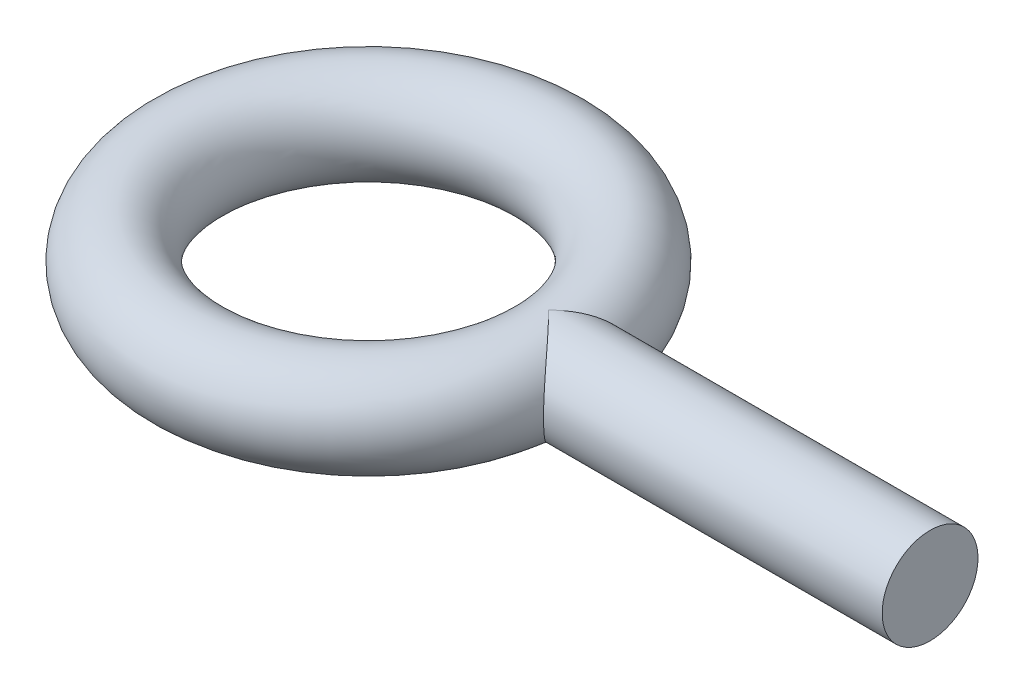
SolidWorks part; units mm, degrees
ref_plane "Front Plane" through (0, 0, 0) normal (0, 0, 1) x (1, 0, 0)
ref_plane "Top Plane" through (0, 0, 0) normal (0, 1, 0) x (1, 0, 0)
ref_plane "Right Plane" through (0, 0, 0) normal (1, 0, 0) x (0, 0, -1)
sketch "layout" plane through (0, 0, 0) normal (0, 1, 0) x (1, 0, 0)
  line L0 (0, 0) -> (37.211, 0) construction
  circle A0 centre (0, 0) radius 15.113 construction
  dimension "D1" = 30.226
  dimension "D2" = 52.324
sketch "Sketch2" plane through (0, 0, 0) normal (0, 0, 1) x (1, 0, 0)
  line L3 (0, 0) -> (0, 6.6909) construction
  line L4 (15.113, 0) -> (-15.113, 0) construction
  circle A0 centre (-11.938, 0) radius 3.175
  point P4 (-15.113, 0)
  dimension "D1" = 6.35
revolve "Revolve1" add sketch "Sketch2" angle 360 about L3
ref_plane "Plane1" through (37.211, 0, 0) normal (1, 0, 0) x (0, 0, -1)
sketch "Sketch3" plane through (37.211, 0, 0) normal (1, 0, 0) x (0, 0, -1)
  circle A0 centre (0, 0) radius 3.175
  dimension "A" = 6.35
extrude "Extrude1" add sketch "Sketch3" against normal up to next
cosmetic thread "Cosmetic Thread1" [suppressed] parameters "D1"=19.05, "D2"=4.7625
sketch "Sketch4" plane through (0, 0, 0) normal (0, 1, 0) x (1, 0, 0)
  line L0 (36.7527, 3.175) -> (37.211, 2.3812)
  line L1 (37.211, 2.3812) -> (37.6693, 3.175)
  line L2 (37.6693, 3.175) -> (37.6693, 4.0915)
  line L3 (37.6693, 4.0915) -> (36.7527, 4.0915)
  line L4 (36.7527, 4.0915) -> (36.7527, 3.175)
  line L5 (0, 0) -> (42.1538, 0) construction
  dimension "D1" = 4.7625
  dimension "D2" = 6.35
revolve "Cut-Revolve1" [suppressed] cut sketch "Sketch4" angle 360 about L5
pattern_linear "LPattern1" [suppressed] count 15 along (1, 0, 0)
equation "\"A@Sketch3\" = \"D1@Sketch2\""
equation "\"D1@Sketch4\" = \"D2@Cosmetic Thread1\""
equation "\"D2@Sketch4\" = \"D1@Sketch2\""
equation "\"D1@LPattern1\" = \"D1@Cosmetic Thread1\" / \"p@LPattern1\""
